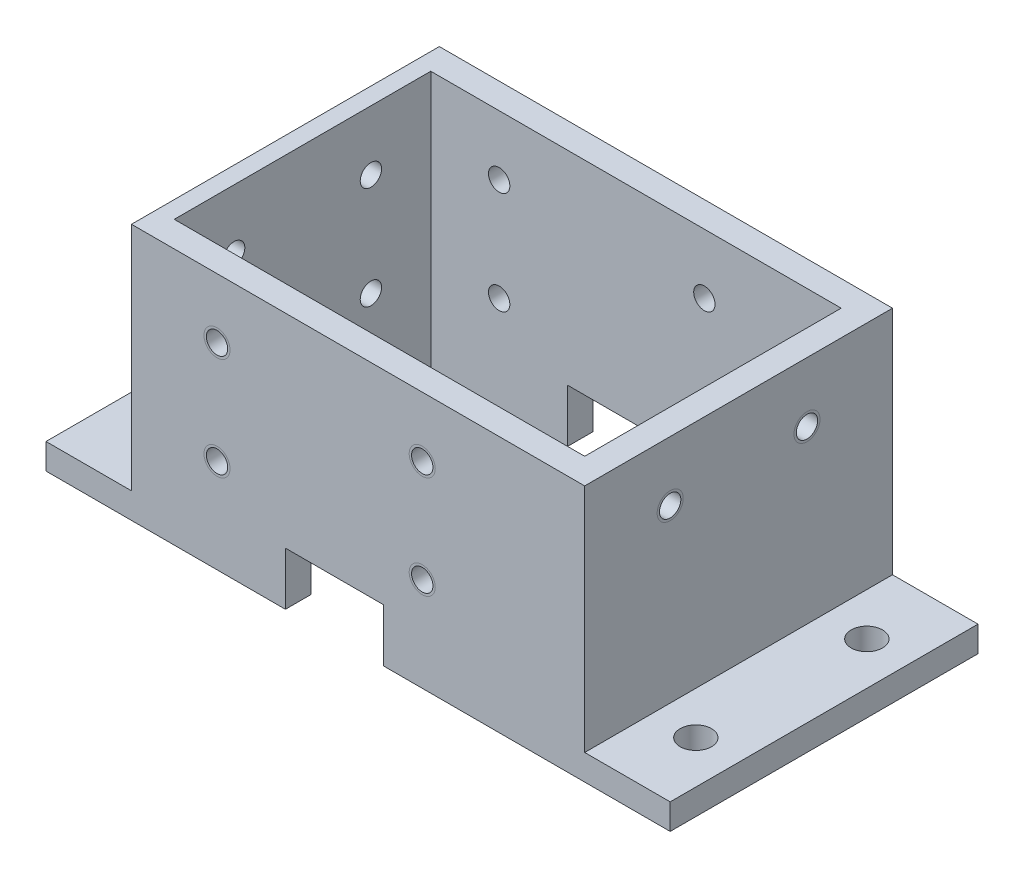
SolidWorks part; units mm, degrees
material "ABS"
ref_plane "Front Plane" through (0, 0, 0) normal (0, 0, 1) x (1, 0, 0)
ref_plane "Top Plane" through (0, 0, 0) normal (0, 1, 0) x (1, 0, 0)
ref_plane "Right Plane" through (0, 0, 0) normal (1, 0, 0) x (0, 0, -1)
sketch "Sketch1" plane through (0, 0, 0) normal (1, 0, 0) x (0, 0, -1)
  line L0 (0, 0) -> (0, 38)
  line L1 (0, 38) -> (36, 38)
  line L2 (36, 38) -> (36, 0)
  line L3 (36, 0) -> (0, 0)
  dimension "D1" = 38
  dimension "D2" = 36
extrude "Boss-Extrude2" add sketch "Sketch1" along normal blind 53
sketch "Sketch3" plane through (53, 0, 0) normal (1, 0, 0) x (0, 0, -1)
  line L0 (36, 0) -> (0, 0) construction
  line L1 (3, 0) -> (3, 35)
  line L2 (3, 35) -> (33, 35)
  line L3 (33, 35) -> (33, 0)
  line L4 (33, 0) -> (3, 0)
  line L5 (0, 38) -> (36, 38) construction
  line L6 (36, 38) -> (36, 0) construction
  line L7 (0, 0) -> (0, 38) construction
  dimension "D1" = 3
  dimension "D2" = 3
  dimension "D3" = 3
extrude "Cut-Extrude1" cut sketch "Sketch3" against normal blind 51
sketch "Sketch4" plane through (0, 0, 0) normal (0, 0, 1) x (1, 0, 0)
  line L0 (50, 0) -> (50, 30)
  line L1 (53, 0) -> (0, 0) construction
  line L2 (50, 30) -> (53, 30)
  line L3 (53, 38) -> (53, 0) construction
  line L4 (53, 30) -> (53, 0)
  line L5 (53, 0) -> (50, 0)
  dimension "D1" = 3
  dimension "D2" = 30
extrude "Boss-Extrude3" add sketch "Sketch4" against normal up to surface (33 mm away) up to face at (27.5, 17.5, -33)
sketch "Sketch5" plane through (0, 0, 0) normal (0, 0, 1) x (1, 0, 0)
  line L0 (53, 30) -> (0, 30)
  line L1 (53, 38) -> (53, 0) construction
  line L2 (0, 30) -> (0, 38)
  line L3 (53, 38) -> (0, 38) construction
  line L4 (0, 38) -> (53, 38)
  line L5 (53, 38) -> (53, 30)
  line L6 (53, 0) -> (0, 0) construction
  line L7 (0, 38) -> (0, 0) construction
  dimension "D1" = 30
  dimension "D2" = 0
extrude "Cut-Extrude2" cut sketch "Sketch5" against normal blind 52
sketch "Sketch6" plane through (0, 0, 0) normal (0, -1, 0) x (-1, 0, 0)
  line L0 (-53, 0) -> (-53, -7)
  line L1 (-53, -7) -> (0, -7)
  line L2 (0, -7) -> (0, 0)
  line L3 (0, 0) -> (-53, 0)
  line L4 (-53, 36) -> (-53, 43)
  line L5 (-53, 43) -> (0, 43)
  line L6 (0, 43) -> (0, 36)
  line L7 (0, 36) -> (-53, 36)
  dimension "D1" = 7
  dimension "D2" = 7
extrude "Boss-Extrude4" add sketch "Sketch6" against normal blind 3
sketch "Sketch8" plane through (0, 0, -43) normal (0, 0, -1) x (-1, 0, 0)
  line L0 (-29.5, 0) -> (-29.5, 3)
  line L1 (0, 0) -> (-53, 0) construction
  line L2 (-53, 3) -> (0, 3) construction
  line L3 (-29.5, 3) -> (-18, 3)
  line L4 (0, 3) -> (-53, 3) construction
  line L5 (-18, 3) -> (-18, 0)
  line L6 (-18, 0) -> (-29.5, 0)
  line L7 (-53, 3) -> (-53, 0) construction
  line L8 (0, 38) -> (0, 0) construction
  dimension "D1" = 23.5
  dimension "D2" = 18
extrude "Cut-Extrude4" cut sketch "Sketch8" against normal through all both and the other way through all
hole_wizard "M3 Tapped Hole1" positions "Sketch38" profile "Sketch35" tap size "M3" standard "AS"
sketch "Sketch38" plane through (0, 0, 0) normal (0, 0, 1) x (1, 0, 0)
  line L0 (0, 30) -> (0, 3) construction
  line L1 (18, 0) -> (0, 0) construction
  point P0 (10, 23)
  dimension "D1" = 10
  dimension "D2" = 23
sketch "Sketch35" plane through (10, 23, 0) normal (1, 0, 0) x (0, -1, 0)
  line L0 (0, 0) -> (0, 3)
  line L1 (0, 3) -> (1.25, 3)
  line L2 (1.25, 3) -> (1.25, 0.0024)
  line L3 (1.25, 0.0024) -> (1.525, 0)
  line L5 (1.525, 0) -> (0, 0)
  line L6 (-1.25, 0.0024) -> (-1.525, 0) construction
  line L11 (0, -6.35) -> (0, 107.95) construction
  dimension "Thru Tap Drill Dia." = 2.5
  dimension "Thru Tap Drill Depth" = 3
  dimension "Near C'Sink Dia." = 3.05
  dimension "Near C'Sink Angle" = 179
cosmetic thread "Hole Thread2" parameters "D2"=3
pattern_linear "LPattern1" count 2 spacing 24 along (1, 0, 0) count 2 spacing 12 along (0, -1, 0) of "M3 Tapped Hole1"
hole_wizard "M3 Tapped Hole2" positions "Sketch39" profile "Sketch40" tap size "M3" standard "AS"
sketch "Sketch39" plane through (0, 0, 0) normal (-1, 0, 0) x (0, 0, 1)
  line L0 (-36, 30) -> (0, 30) construction
  line L1 (-36, 3) -> (-36, 30) construction
  point P0 (-26, 23)
  dimension "D1" = 7
  dimension "D2" = 10
sketch "Sketch40" plane through (0, 23, -26) normal (0, 1, 0) x (0, 0, 1)
  line L0 (0, 0) -> (0, 2)
  line L1 (0, 2) -> (1.25, 2)
  line L2 (1.25, 2) -> (1.25, 0.0024)
  line L3 (1.25, 0.0024) -> (1.525, 0)
  line L5 (1.525, 0) -> (0, 0)
  line L6 (-1.25, 0.0024) -> (-1.525, 0) construction
  line L11 (0, -6.35) -> (0, 107.95) construction
  dimension "Thru Tap Drill Dia." = 2.5
  dimension "Thru Tap Drill Depth" = 2
  dimension "Near C'Sink Dia." = 3.05
  dimension "Near C'Sink Angle" = 179
cosmetic thread "Hole Thread3" parameters "D2"=3
pattern_linear "LPattern2" count 2 spacing 16 along (0, 0, 1) count 2 spacing 12 along (0, -1, 0) of "M3 Tapped Hole2"
hole_wizard "M3 Tapped Hole3" positions "Sketch41" profile "Sketch42" tap size "M3" standard "AS" end condition up to next
sketch "Sketch41" plane through (53, 0, 0) normal (1, 0, 0) x (0, 0, -1)
  line L0 (36, 30) -> (0, 30) construction
  line L1 (36, 3) -> (36, 30) construction
  point P0 (26, 23)
  dimension "D1" = 7
  dimension "D2" = 10
sketch "Sketch42" plane through (53, 23, -26) normal (0, 1, 0) x (0, 0, -1)
  line L0 (0, 0) -> (0, 3)
  line L1 (0, 3) -> (1.25, 3)
  line L2 (1.25, 3) -> (1.25, 0.0024)
  line L3 (1.25, 0.0024) -> (1.525, 0)
  line L5 (1.525, 0) -> (0, 0)
  line L6 (-1.25, 0.0024) -> (-1.525, 0) construction
  line L11 (0, -6.35) -> (0, 107.95) construction
  dimension "Thru Tap Drill Dia." = 2.5
  dimension "Thru Tap Drill Depth" = 3
  dimension "Near C'Sink Dia." = 3.05
  dimension "Near C'Sink Angle" = 179
cosmetic thread "Hole Thread4" parameters "D2"=3
pattern_linear "LPattern3" count 2 spacing 16 along (0, 0, 1) of "M3 Tapped Hole3"
hole_wizard "M3 Tapped Hole4" positions "Sketch43" profile "Sketch44" tap size "M3" standard "AS" end condition up to next
sketch "Sketch43" plane through (0, 0, -36) normal (0, 0, -1) x (-1, 0, 0)
  line L0 (0, 30) -> (-53, 30) construction
  line L1 (0, 3) -> (0, 30) construction
  point P0 (-10, 23)
  dimension "D1" = 7
  dimension "D2" = 10
sketch "Sketch44" plane through (10, 23, -36) normal (1, 0, 0) x (0, 1, 0)
  line L0 (0, 0) -> (0, 3)
  line L1 (0, 3) -> (1.25, 3)
  line L2 (1.25, 3) -> (1.25, 0.0024)
  line L3 (1.25, 0.0024) -> (1.525, 0)
  line L5 (1.525, 0) -> (0, 0)
  line L6 (-1.25, 0.0024) -> (-1.525, 0) construction
  line L11 (0, -6.35) -> (0, 107.95) construction
  dimension "Thru Tap Drill Dia." = 2.5
  dimension "Thru Tap Drill Depth" = 3
  dimension "Near C'Sink Dia." = 3.05
  dimension "Near C'Sink Angle" = 179
cosmetic thread "Hole Thread5" parameters "D2"=3
pattern_linear "LPattern4" count 2 spacing 24 along (1, 0, 0) count 2 spacing 12 along (0, -1, 0) of "M3 Tapped Hole4"
sketch "Sketch45" plane through (0, 3, 0) normal (0, 1, 0) x (1, 0, 0)
  line L0 (0, 36) -> (53, 36) construction
  line L1 (18, 43) -> (18, 36) construction
  circle A0 centre (8, 39.5) radius 1.8333
  dimension "D1" = 3.6667
  dimension "D2" = 3.5
  dimension "D3" = 10
extrude "Cut-Extrude5" cut sketch "Sketch45" against normal through all both and the other way through all
pattern_linear "LPattern5" count 2 spacing 35 along (1, 0, 0) count 2 spacing 43 along (0, 0, 1) of "Cut-Extrude5"
sketch "Sketch46" plane through (0, 0, -36) normal (0, 0, -1) x (-1, 0, 0)
  line L0 (-29.5, 3) -> (-29.5, 6.2)
  line L1 (-29.5, 6.2) -> (-18, 6.2)
  line L2 (-18, 6.2) -> (-18, 3)
  line L3 (-29.5, 3) -> (-18, 3)
  dimension "D1" = 3.2
extrude "Cut-Extrude6" cut sketch "Sketch46" against normal through all both and the other way through all
sketch "Sketch47" plane through (0, 3, 0) normal (0, 1, 0) x (1, 0, 0)
  line L0 (0, 43) -> (0, 36)
  line L1 (0, 36) -> (53, 36)
  line L2 (53, 36) -> (53, 43)
  line L3 (53, 43) -> (0, 43)
  line L4 (0, 0) -> (0, -7)
  line L5 (0, -7) -> (53, -7)
  line L6 (53, -7) -> (53, 0)
  line L7 (53, 0) -> (0, 0)
extrude "Cut-Extrude7" cut sketch "Sketch47" against normal through all both and the other way through all
sketch "Sketch49" plane through (0, 30, 0) normal (0, 1, 0) x (1, 0, 0)
  line L0 (0, 36) -> (-10, 36)
  line L1 (-10, 36) -> (-10, 0)
  line L2 (-10, 0) -> (0, 0)
  line L3 (0, 0) -> (0, 36)
  line L4 (53, 36) -> (63, 36)
  line L5 (63, 36) -> (63, 0)
  line L6 (63, 0) -> (53, 0)
  line L7 (53, 0) -> (53, 36)
  dimension "D1" = 10
  dimension "D2" = 10
extrude "Boss-Extrude5" add sketch "Sketch49" along normal blind 3 from surface at -30 starting at face at (40.5, 0, -18)
sketch "Sketch50" plane through (0, 3, 0) normal (0, 1, 0) x (1, 0, 0)
  line L0 (-10, 36) -> (-10, 0) construction
  line L1 (63, 0) -> (63, 36) construction
  line L2 (63, 36) -> (53, 36) construction
  line L3 (53, 0) -> (63, 0) construction
  line L4 (-10, 0) -> (0, 0) construction
  line L5 (0, 36) -> (-10, 36) construction
  circle A0 centre (-5, 28) radius 1.835
  circle A1 centre (-5, 8) radius 1.835
  circle A2 centre (58, 8) radius 1.835
  circle A3 centre (58, 28) radius 1.835
  dimension "D1" = 3.67
  dimension "D2" = 3.67
  dimension "D3" = 3.67
  dimension "D4" = 3.67
  dimension "D5" = 5
  dimension "D6" = 5
  dimension "D7" = 5
  dimension "D8" = 5
  dimension "D9" = 8
  dimension "D10" = 8
  dimension "D11" = 8
  dimension "D12" = 8
extrude "Cut-Extrude8" cut sketch "Sketch50" against normal through all both and the other way through all
